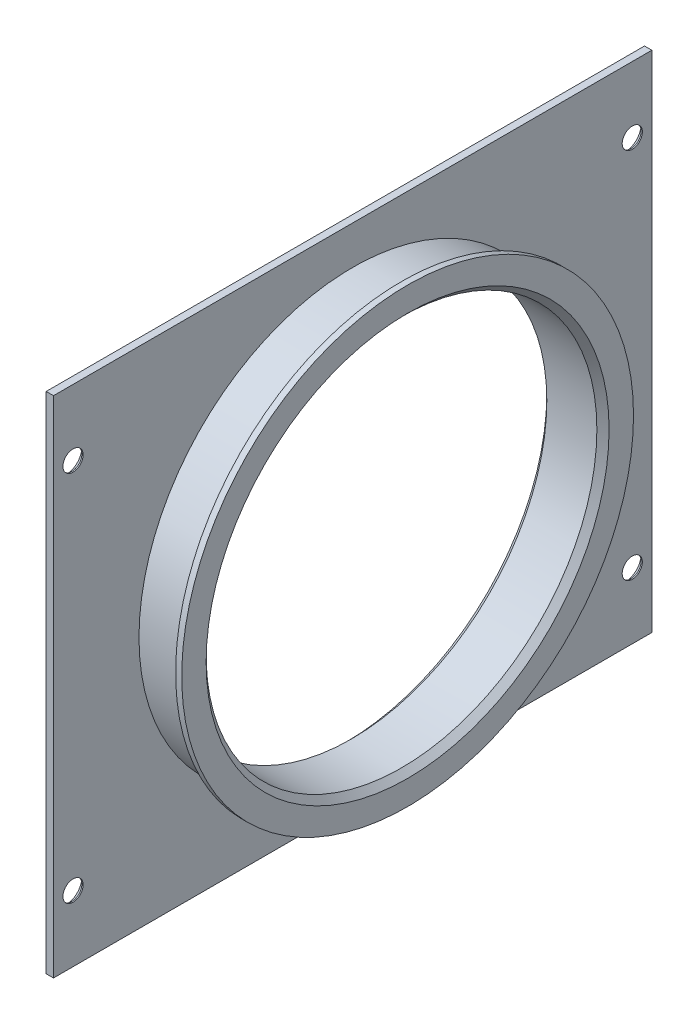
SolidWorks part; units mm, degrees
ref_plane "Front Plane" through (0, 0, 0) normal (1, 0, 0) x (0, 1, 0)
ref_plane "Top Plane" through (0, 0, 0) normal (0, 0, 1) x (0, 1, 0)
ref_plane "Right Plane" through (0, 0, 0) normal (0, 1, 0) x (-1, 0, 0)
sketch "Sketch1" plane through (0, 0, 0) normal (1, 0, 0) x (0, 1, 0)
  line L1 (0, 0) -> (82.6, 0)
  line L2 (0, 0) -> (0, 98)
  line L3 (0, 98) -> (82.6, 98)
  line L4 (82.6, 0) -> (82.6, 98)
  dimension "D1" = 98
  dimension "D2" = 82.6
extrude "Boss-Extrude1" add sketch "Sketch1" along normal blind 1.2
sketch "Sketch2" plane through (1.2, 0, 0) normal (1, 0, 0) x (0, 1, 0)
  line L0 (0, 0) -> (82.6, 0) construction
  line L1 (10.8, 94.8) -> (71.8, 94.8) construction
  line L2 (10.8, 94.8) -> (10.8, 3.2) construction
  line L3 (10.8, 3.2) -> (71.8, 3.2) construction
  line L4 (71.8, 94.8) -> (71.8, 3.2) construction
  line L5 (0, 98) -> (0, 0) construction
  circle A0 centre (10.8, 94.8) radius 1.65
  circle A1 centre (71.8, 94.8) radius 1.65
  circle A2 centre (10.8, 3.2) radius 1.65
  circle A3 centre (71.8, 3.2) radius 1.65
  dimension "D5" = 3.3
  dimension "D1" = 91.6
  dimension "D2" = 61
  dimension "D3" = 3.2
  dimension "D4" = 10.8
extrude "Cut-Extrude1" cut sketch "Sketch2" against normal through all
sketch "Sketch3" plane through (1.2, 0, 0) normal (1, 0, 0) x (0, 1, 0)
  line L0 (0, 98) -> (82.6, 0) construction
  line L1 (0, 0) -> (82.6, 98) construction
  circle A0 centre (41.3, 49) radius 35
  dimension "D1" = 70
extrude "Boss-Extrude2" add sketch "Sketch3" along normal blind 8
sketch "Sketch4" plane through (9.2, 0, 0) normal (1, 0, 0) x (0, 1, 0)
  circle A0 centre (41.3, 49) radius 37
  circle A1 centre (41.3, 49) radius 35 construction
  dimension "D1" = 74
extrude "Boss-Extrude3" add sketch "Sketch4" along normal blind 1 contours A0
sketch "Sketch5" plane through (10.2, 0, 0) normal (1, 0, 0) x (0, 1, 0)
  circle A0 centre (41.3, 49) radius 32
  circle A1 centre (41.3, 49) radius 37 construction
  dimension "D1" = 64
extrude "Cut-Extrude2" cut sketch "Sketch5" against normal through all
chamfer "Chamfer1" distance 1 angle 45 4 edges at (0, 10.8, 1.55) (0, 71.8, 1.55) (0, 10.8, 93.15) (0, 71.8, 93.15)
chamfer "Chamfer2" distance 1 angle 45 2 edges at (0, 41.3, 17) (10.2, 41.3, 17)
